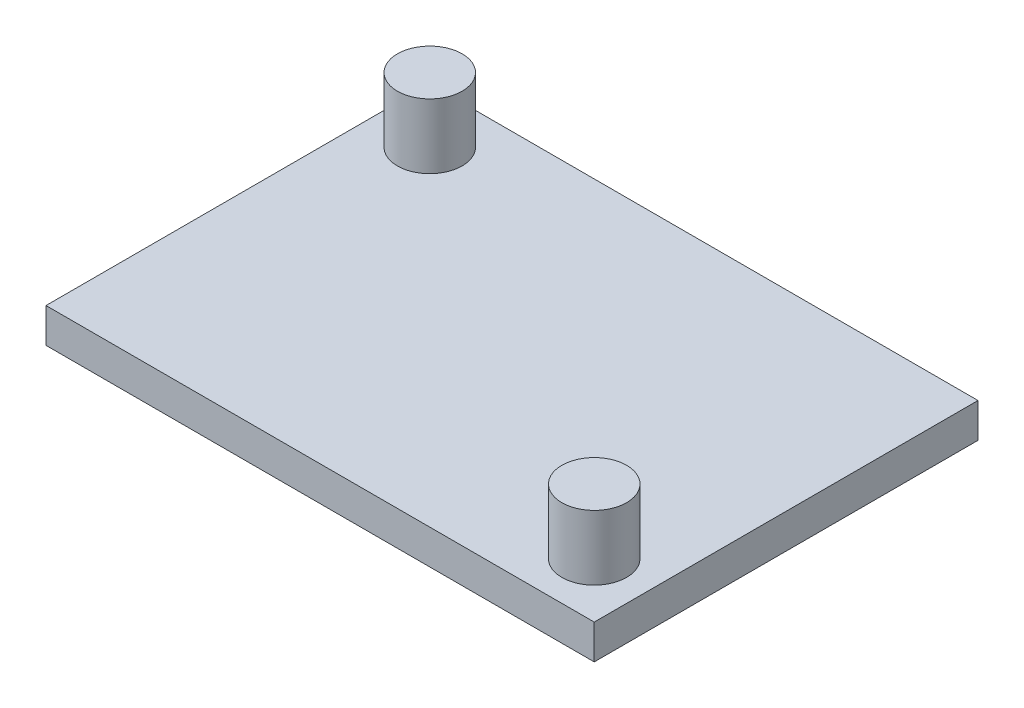
SolidWorks part; units mm, degrees
ref_plane "Front Plane" through (0, 0, 0) normal (0, 0, 1) x (1, 0, 0)
ref_plane "Top Plane" through (0, 0, 0) normal (0, 1, 0) x (1, 0, 0)
ref_plane "Right Plane" through (0, 0, 0) normal (1, 0, 0) x (0, 0, -1)
sketch "SK_P01_Standoff" plane through (0, 0, 0) normal (0, 1, 0) x (1, 0, 0)
  circle A0 centre (-10.16, 6.35) radius 1.5
extrude "P01_Standoff" add sketch "SK_P01_Standoff" along normal blind 3 from offset 3
sketch "SK_P02_Standoff" plane through (0, 0, 0) normal (0, 1, 0) x (1, 0, 0)
  circle A0 centre (10.16, -6.35) radius 1.5
extrude "P02_Standoff" add sketch "SK_P02_Standoff" along normal blind 3 from offset 3
sketch "SK_P03_VL53L4CDboard" plane through (0, 0, 0) normal (0, 1, 0) x (1, 0, 0)
  line L0 (-12.7, -8.89) -> (12.7, -8.89)
  line L1 (12.7, -8.89) -> (12.7, 8.89)
  line L2 (12.7, 8.89) -> (-12.7, 8.89)
  line L3 (-12.7, 8.89) -> (-12.7, -8.89)
extrude "P03_VL53L4CDboard" add sketch "SK_P03_VL53L4CDboard" along normal blind 1.6 from offset 1.4
sketch "SK_P04_ToFsensor" plane through (0, 0, 0) normal (0, 1, 0) x (1, 0, 0)
  line L0 (-2.5, -1.5) -> (2.5, -1.5)
  line L1 (2.5, -1.5) -> (2.5, 1.5)
  line L2 (2.5, 1.5) -> (-2.5, 1.5)
  line L3 (-2.5, 1.5) -> (-2.5, -1.5)
extrude "P04_ToFsensor" add sketch "SK_P04_ToFsensor" along normal blind 1.4
